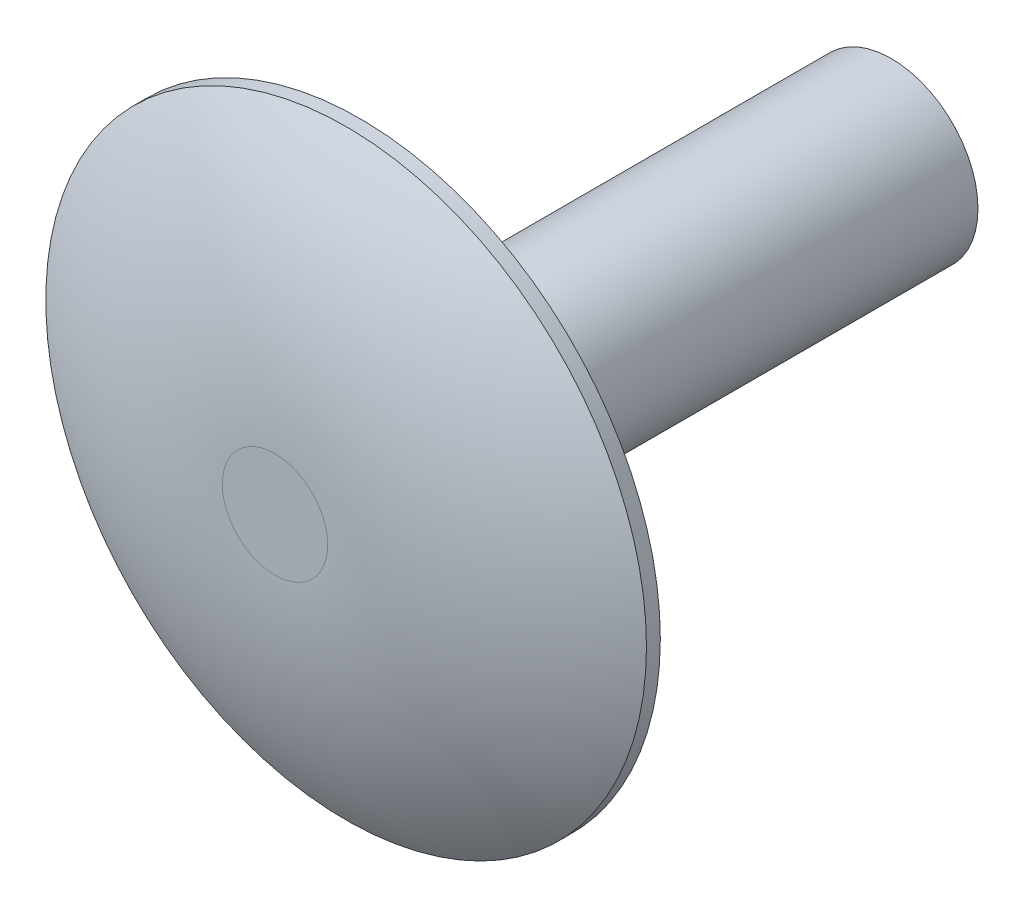
SolidWorks part; units mm, degrees
material "6061 Alloy"
ref_plane "Front Plane" through (0, 0, 0) normal (0, 0, 1) x (1, 0, 0)
ref_plane "Top Plane" through (0, 0, 0) normal (0, 1, 0) x (1, 0, 0)
ref_plane "Right Plane" through (0, 0, 0) normal (1, 0, 0) x (0, 0, -1)
sketch "Sketch1" plane through (0, 0, 0) normal (0, 0, 1) x (1, 0, 0)
  circle A0 centre (0, 0) radius 8.255
  dimension "D1" = 16.51
extrude "Boss-Extrude1" add sketch "Sketch1" along normal blind 2.3368
sketch "Sketch2" plane through (0, 0, 0) normal (0, 0, 1) x (1, 0, 0)
  circle A0 centre (0, 0) radius 2.3813
  dimension "D1" = 4.7625
extrude "Boss-Extrude2" add sketch "Sketch2" against normal blind 14.605
sketch "Sketch3" plane through (0, 0, 0) normal (0, 1, 0) x (1, 0, 0)
  line L0 (0, -2.3368) -> (1.4478, -2.3368)
  line L1 (-8.255, -2.3368) -> (8.255, -2.3368) construction
  line L2 (0, -2.3368) -> (0, 0) construction
  line L3 (8.255, -2.3368) -> (8.255, 0) construction
  line L4 (8.255, -0.381) -> (8.255, 0)
  line L5 (8.255, 0) -> (-8.255, 0) construction
  line L6 (8.255, -0.381) -> (8.255, -2.3368)
  line L7 (8.255, -2.3368) -> (1.4478, -2.3368)
  arc A0 (1.4478, -2.3368) -> (8.255, -0.381) centre (1.4478, 10.4874) ccw
  dimension "D1" = 2.8956
  dimension "D2" = 0.381
revolve "Cut-Revolve1" cut sketch "Sketch3" angle 360 about L2
